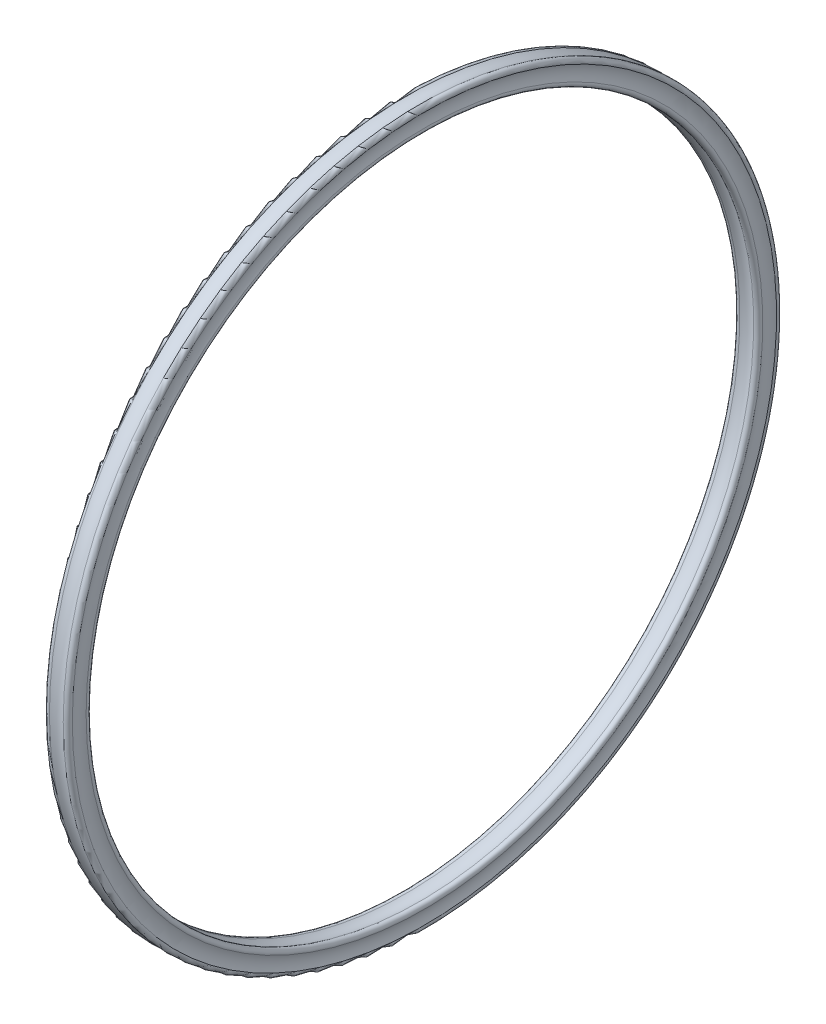
SolidWorks part; units mm, degrees
ref_plane "Front Plane" through (0, 0, 0) normal (0, 0, 1) x (1, 0, 0)
ref_plane "Top Plane" through (0, 0, 0) normal (0, 1, 0) x (1, 0, 0)
ref_plane "Right Plane" through (0, 0, 0) normal (1, 0, 0) x (0, 0, -1)
sketch "Sketch1" plane through (0, 0, 0) normal (0, 0, 1) x (1, 0, 0)
  line L0 (-0.889, 0) -> (0.889, 0) construction
  line L1 (-0.889, 27.0383) -> (0.889, 27.0383) construction
  line L2 (-0.889, 27.0383) -> (-0.889, 25.2603) construction
  line L3 (-0.889, 25.2603) -> (0.889, 25.2603) construction
  line L4 (0.889, 27.0383) -> (0.889, 25.2603) construction
  line L5 (-0.889, 25.2603) -> (0.889, 27.0383) construction
  line L9 (0.7557, 26.1493) -> (0.7557, 25.2603) construction
  line L11 (0.889, 25.2603) -> (0.889, -25.2603) construction
  line L12 (-0.889, 27.0383) -> (-0.889, -27.0383) construction
  circle A0 centre (0, 26.1493) radius 0.7557 construction
  arc A1 (-0.8666, 26.6722) -> (-0.8666, 25.6264) centre (-2.0436, 26.1493) cw
  arc A2 (-0.5229, 27.0159) -> (0.5229, 27.0159) centre (0, 28.1929) ccw
  arc A3 (-0.8666, 26.6722) -> (-0.5229, 27.0159) centre (-0.6286, 26.7779) cw
  arc A4 (0.8666, 26.6722) -> (0.8666, 25.6264) centre (2.0436, 26.1493) ccw
  arc A5 (-0.5229, 25.2827) -> (0.5229, 25.2827) centre (0, 24.1057) cw
  arc A6 (0.5229, 27.0159) -> (0.8666, 26.6722) centre (0.6286, 26.7779) cw
  arc A7 (-0.8666, 25.6264) -> (-0.5229, 25.2827) centre (-0.6286, 25.5207) ccw
  arc A8 (0.5229, 25.2827) -> (0.8666, 25.6264) centre (0.6286, 25.5207) ccw
  circle A9 centre (0, 26.1493) radius 0.889 construction
  dimension "D1" = 1.5113
revolve "Revolve1" add sketch "Sketch1" angle 360 mid plane about L0
equation "\"D1@Sketch1\" = \"Width@Sketch1\"*.85"
